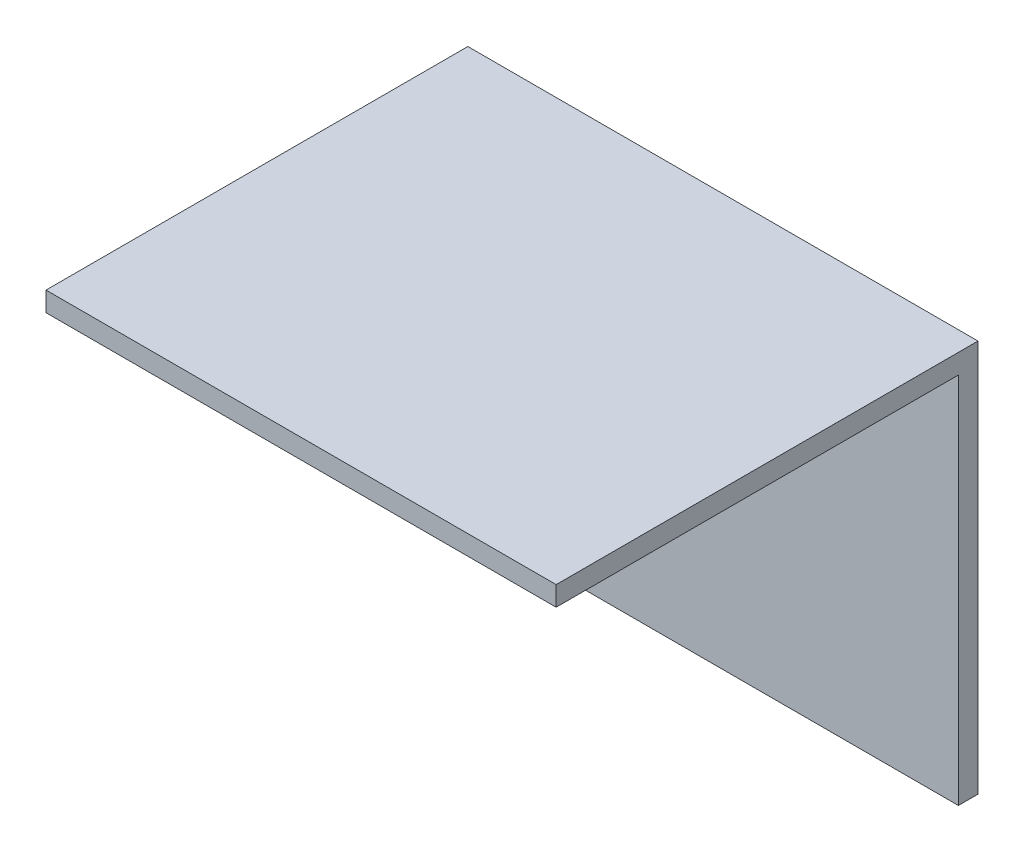
SolidWorks part; units mm, degrees
ref_plane "Plan de face" through (0, 0, 0) normal (0, 0, 1) x (1, 0, 0)
ref_plane "Plan de dessus" through (0, 0, 0) normal (0, 1, 0) x (1, 0, 0)
ref_plane "Plan de droite" through (0, 0, 0) normal (1, 0, 0) x (0, 0, -1)
sketch "Esquisse1" plane through (0, 0, 0) normal (0, 0, 1) x (1, 0, 0)
  line L1 (-26, -20) -> (26, -20)
  line L2 (-26, -20) -> (-26, 20)
  line L3 (-26, 20) -> (26, 20)
  line L4 (26, -20) -> (26, 20)
  line L5 (-26, -20) -> (26, 20) construction
  line L6 (-26, 20) -> (26, -20) construction
  point P0 (0, 0)
  dimension "D1" = 40
  dimension "D2" = 52
extrude "Boss.-Extru.1" add sketch "Esquisse1" along normal blind 43
sketch "Esquisse2" plane through (-26, 0, 0) normal (-1, 0, 0) x (0, 0, 1)
  line L8 (2, -18) -> (41, -18)
  line L9 (41, -18) -> (41, 18)
  line L10 (41, 18) -> (2, 18)
  line L11 (2, 18) -> (2, -18)
  line L12 (2, -18) -> (50.222, -18)
  line L13 (50.222, -18) -> (50.222, 18)
  line L14 (50.222, 18) -> (2, 18)
  line L15 (2, 18) -> (2, -18)
  dimension "D1" = 2
extrude "Enlèv. mat.-Extru.1" cut sketch "Esquisse2" against normal blind 50
sketch "Esquisse3" plane through (0, -20, 0) normal (0, -1, 0) x (1, 0, 0)
  line L8 (-24, 2) -> (24, 2)
  line L9 (24, 2) -> (24, 41)
  line L10 (24, 41) -> (-24, 41)
  line L11 (-24, 41) -> (-24, 2)
  line L12 (-34.6852, 2) -> (38.0009, 2)
  line L13 (38.0009, 2) -> (38.0009, 52.5344)
  line L14 (38.0009, 52.5344) -> (-34.6852, 52.5344)
  line L15 (-34.6852, 52.5344) -> (-34.6852, 2)
  dimension "D1" = 2
extrude "Enlèv. mat.-Extru.2" cut sketch "Esquisse3" against normal up to surface (38 mm away) up to face at (-1, 18, 22.5)
